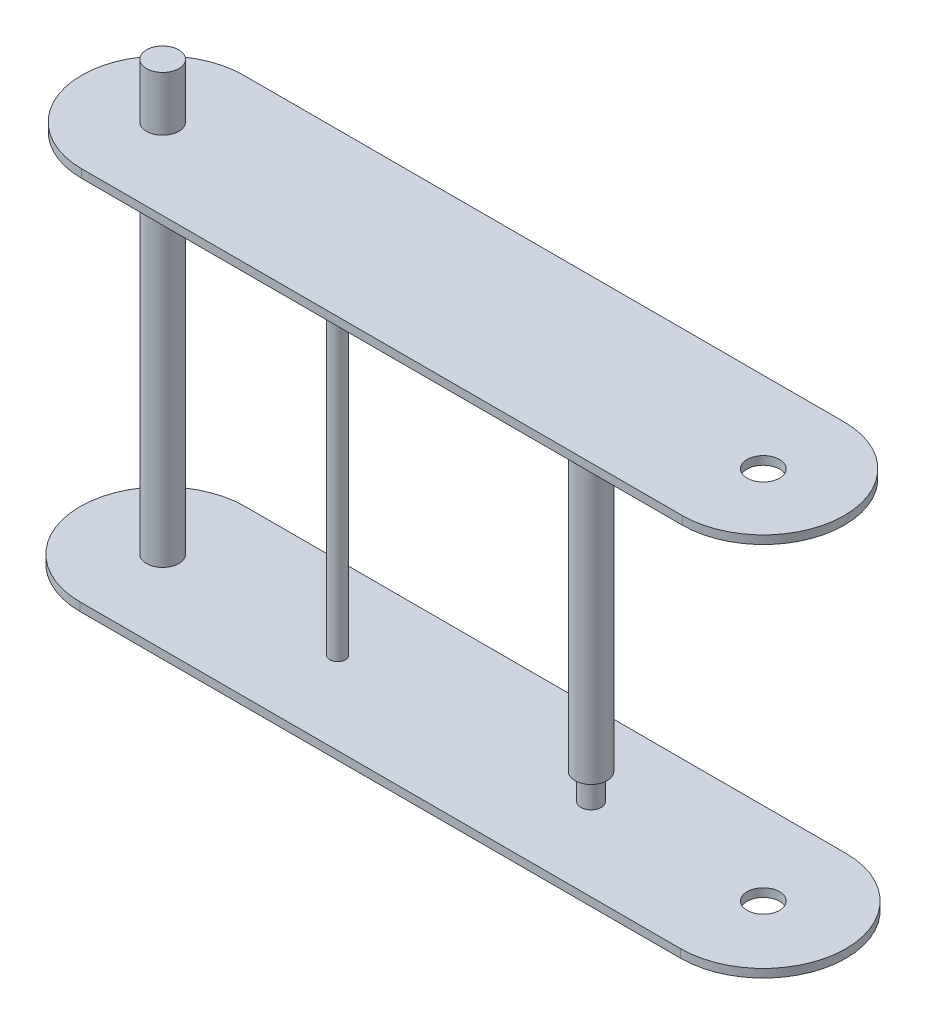
SolidWorks part; units mm, degrees
ref_plane "Front Plane" through (0, 0, 0) normal (0, 0, 1) x (1, 0, 0)
ref_plane "Top Plane" through (0, 0, 0) normal (0, 1, 0) x (1, 0, 0)
ref_plane "Right Plane" through (0, 0, 0) normal (1, 0, 0) x (0, 0, -1)
sketch "Sketch1" plane through (0, 0, 0) normal (0, 1, 0) x (1, 0, 0)
  line L0 (-110.5891, 0) -> (119.2109, 0) construction
  line L1 (-110.5891, 31.6) -> (119.2109, 31.6)
  line L2 (-110.5891, -31.6) -> (119.2109, -31.6)
  arc A0 (-110.5891, 31.6) -> (-110.5891, -31.6) centre (-110.5891, 0) ccw
  arc A1 (119.2109, -31.6) -> (119.2109, 31.6) centre (119.2109, 0) ccw
  circle A2 centre (119.2109, 0) radius 6.2
  point P3 (4.3109, 0)
  point P8 (-142.1891, 0)
  point P9 (150.8109, 0)
  dimension "D3" = 12.4
  dimension "D1" = 63.2
  dimension "D2" = 293
extrude "Boss-Extrude1" add sketch "Sketch1" along normal blind 3.2
ref_plane "Plane4" through (0, 143.2, 0) normal (0, 1, 0) x (1, 0, 0)
sketch "Sketch8" plane through (0, 3.2, 0) normal (0, 1, 0) x (1, 0, 0)
  line L0 (-110.5891, 31.6) -> (-110.5891, -31.6) construction
  line L1 (-142.1891, 0) -> (150.8109, 0) construction
  arc A0 (-110.5891, 31.6) -> (-110.5891, -31.6) centre (-110.5891, 0) ccw construction
  arc A1 (119.2109, -31.6) -> (119.2109, 31.6) centre (119.2109, 0) ccw construction
  circle A2 centre (-110.5891, 0) radius 6.15
  dimension "D1" = 12.3
extrude "Boss-Extrude5" add sketch "Sketch8" along normal blind 140
sketch "Sketch11" plane through (0, 143.2, 0) normal (0, 1, 0) x (1, 0, 0)
  line L0 (-142.1891, 0) -> (150.8109, 0) construction
  line L3 (119.2109, 31.6) -> (119.2109, -31.6) construction
  line L4 (-110.5891, 31.6) -> (-110.5891, -31.6) construction
  line L5 (4.3109, 31.6) -> (4.3109, -31.6) construction
  line L6 (119.2109, 31.6) -> (-110.5891, 31.6) construction
  line L7 (-110.5891, -31.6) -> (119.2109, -31.6) construction
  line L8 (-110.5891, 0) -> (119.2109, 0) construction
  line L9 (-110.5891, 30.9882) -> (119.2109, 30.9882)
  line L10 (-110.5891, -30.9882) -> (119.2109, -30.9882)
  arc A2 (-110.5891, 31.6) -> (-110.5891, -31.6) centre (-110.5891, 0) ccw construction
  arc A3 (119.2109, -31.6) -> (119.2109, 31.6) centre (119.2109, 0) ccw construction
  arc A4 (-110.5891, 30.9882) -> (-110.5891, -30.9882) centre (-110.5891, 0) ccw
  arc A5 (119.2109, -30.9882) -> (119.2109, 30.9882) centre (119.2109, 0) ccw
  circle A6 centre (119.2109, 0) radius 6.2
  point P24 (4.3109, 0)
  dimension "D1" = 12.4
extrude "Boss-Extrude6" add sketch "Sketch11" along normal blind 3.2
sketch "Sketch12" plane through (0, 3.2, 0) normal (0, 1, 0) x (1, 0, 0)
  line L0 (-141.5773, 0) -> (150.8109, 0) construction
  line L1 (-110.5891, 31.6) -> (-110.5891, -30.9882) construction
  line L2 (-43.6391, 31.6) -> (-43.6391, -31.6) construction
  line L3 (119.2109, 31.6) -> (-110.5891, 31.6) construction
  line L4 (-110.5891, -31.6) -> (119.2109, -31.6) construction
  arc A0 (-110.5891, 30.9882) -> (-110.5891, -30.9882) centre (-110.5891, 0) ccw construction
  arc A1 (119.2109, -31.6) -> (119.2109, 31.6) centre (119.2109, 0) ccw construction
  circle A2 centre (-43.6391, 0) radius 3
  dimension "D1" = 6
  dimension "D2" = 66.95
extrude "Boss-Extrude7" add sketch "Sketch12" along normal blind 140
sketch "Sketch14" plane through (0, 3.2, 0) normal (0, 1, 0) x (1, 0, 0)
  line L0 (-141.5773, 0) -> (150.1991, 0) construction
  line L1 (53.3109, 30.9882) -> (53.3109, -30.9882) construction
  line L2 (119.2109, 30.9882) -> (-110.5891, 30.9882) construction
  line L3 (-110.5891, -30.9882) -> (119.2109, -30.9882) construction
  line L4 (-110.5891, 30.9882) -> (-110.5891, -31.6) construction
  arc A0 (-110.5891, 30.9882) -> (-110.5891, -30.9882) centre (-110.5891, 0) ccw construction
  arc A1 (119.2109, -30.9882) -> (119.2109, 30.9882) centre (119.2109, 0) ccw construction
  circle A2 centre (53.3109, 0) radius 3.9
  dimension "D2" = 7.8
  dimension "D1" = 163.9
extrude "Boss-Extrude8" add sketch "Sketch14" along normal blind 10
sketch "Sketch15" plane through (0, 13.2, 0) normal (0, 1, 0) x (1, 0, 0)
  circle A0 centre (53.3109, 0) radius 6.15
  dimension "D1" = 12.3
extrude "Boss-Extrude9" add sketch "Sketch15" along normal blind 60
ref_plane "Plane6" through (0, 73.2, 0) normal (0, 1, 0) x (1, 0, 0)
mirror "Mirror7" about plane through (0, 73.2, 0) normal (0, 1, 0) of "Boss-Extrude8", "Boss-Extrude9"
ref_plane "Plane7" through (0, 73.2, 0) normal (0, -1, 0) x (-1, 0, 0)
sketch "Sketch16" plane through (0, 73.2, 0) normal (0, -1, 0) x (-1, 0, 0)
  circle A0 centre (110.5891, 0) radius 6.2
  dimension "D1" = 12.4
extrude "Boss-Extrude10" add sketch "Sketch16" along normal mid plane 188
